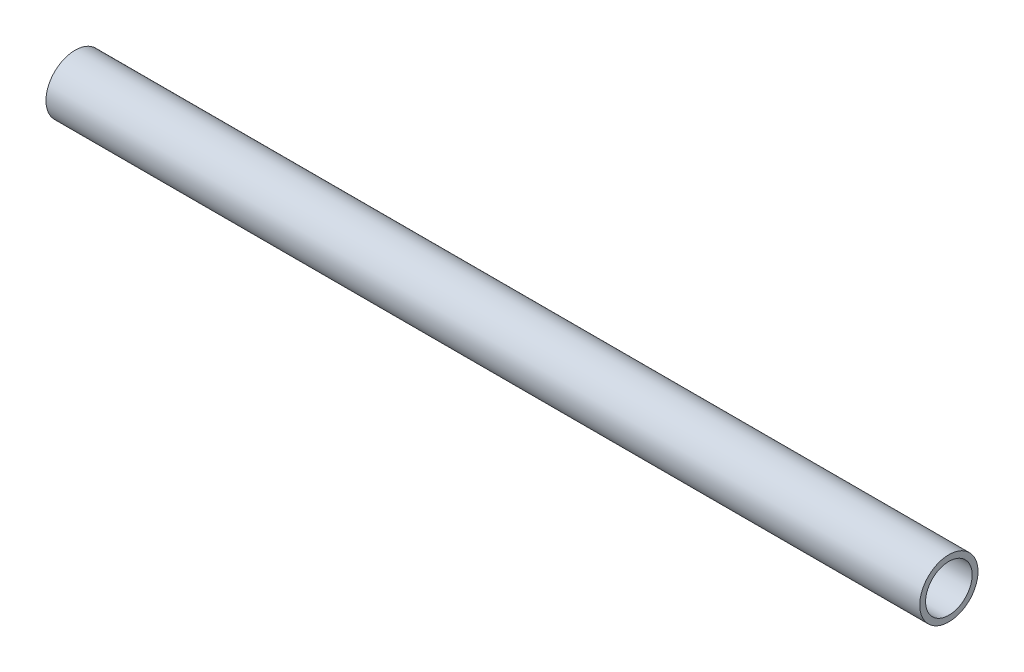
SolidWorks part; units mm, degrees
ref_plane "Front Plane" through (0, 0, 0) normal (0, 0, 1) x (1, 0, 0)
ref_plane "Top Plane" through (0, 0, 0) normal (0, 1, 0) x (1, 0, 0)
ref_plane "Right Plane" through (0, 0, 0) normal (1, 0, 0) x (0, 0, -1)
sketch "Sketch1" plane through (0, 0, 0) normal (1, 0, 0) x (0, 0, -1)
  circle A0 centre (0, 0) radius 8
  circle A1 centre (0, 0) radius 10
  dimension "D1" = 20
  dimension "D2" = 16
extrude "Boss-Extrude1" add sketch "Sketch1" along normal blind 300
